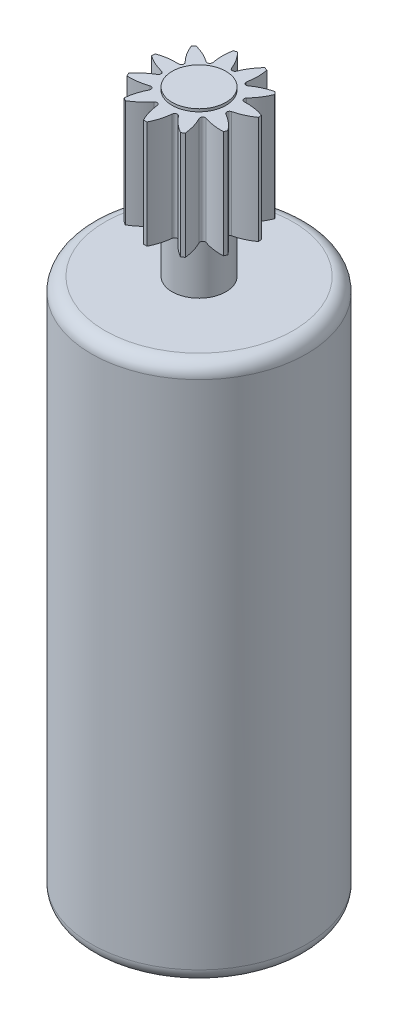
SolidWorks part; units mm, degrees
ref_plane "Front Plane" through (0, 0, 0) normal (0, 0, 1) x (1, 0, 0)
ref_plane "Top Plane" through (0, 0, 0) normal (0, 1, 0) x (1, 0, 0)
ref_plane "Right Plane" through (0, 0, 0) normal (1, 0, 0) x (0, 0, -1)
sketch "Sketch2" plane through (0, 0, 0) normal (0, 0, 1) x (1, 0, 0)
  line L0 (0, 0) -> (0, 26.1)
  line L1 (0, -55) -> (0, 55) construction
  line L2 (0, 0) -> (4, 0)
  line L3 (55, 0) -> (-55, 0) construction
  line L4 (4, 0) -> (4, 20)
  line L5 (4, 20) -> (1, 20)
  line L6 (1, 20) -> (1, 22)
  line L7 (1, 22) -> (2, 22)
  line L8 (2, 22) -> (2, 26)
  line L9 (2, 26) -> (1, 26)
  line L10 (0, 26.1) -> (1, 26.1)
  line L11 (1, 26) -> (1, 26.1)
  dimension "D1" = 26.1
  dimension "D2" = 4
  dimension "D3" = 20
  dimension "D4" = 3
  dimension "D5" = 2
  dimension "D6" = 1
  dimension "D7" = 4
  dimension "D8" = 1
  dimension "D9" = 0.1
revolve "Revolve1" add sketch "Sketch2" angle 360 about L0
fillet "Fillet1" radius 0.5 2 edges at (0, 0, -4) (0, 20, -4)
sketch "Sketch5" plane through (0, 26, 0) normal (0, 1, 0) x (1, 0, 0)
  line L0 (0, -4.4) -> (0, 4.4) construction
  line L1 (0, 1) -> (0, 2.2681) construction
  arc A0 (-0.0929, 1.2999) -> (-0.5, 1.9365) centre (-1.951, 0.5601) ccw
  circle A1 centre (0, 0) radius 1 construction
  circle A2 centre (0, 0) radius 2 construction
  arc A3 (0.0929, 1.2999) -> (0.5, 1.9365) centre (1.951, 0.5601) cw
  arc A4 (-0.0929, 1.2999) -> (0.0929, 1.2999) centre (0, 1.3369) ccw
  dimension "D2" = 2
  dimension "D3" = 2
  dimension "D4" = 0.1
  dimension "D1" = 1
extrude "Cut-Extrude1" cut sketch "Sketch5" against normal blind 4 and the other way through all
pattern_circular "CirPattern1" count 11 over 360 about axis through (0, 26, 0) along (0, -1, 0) of "Cut-Extrude1"
